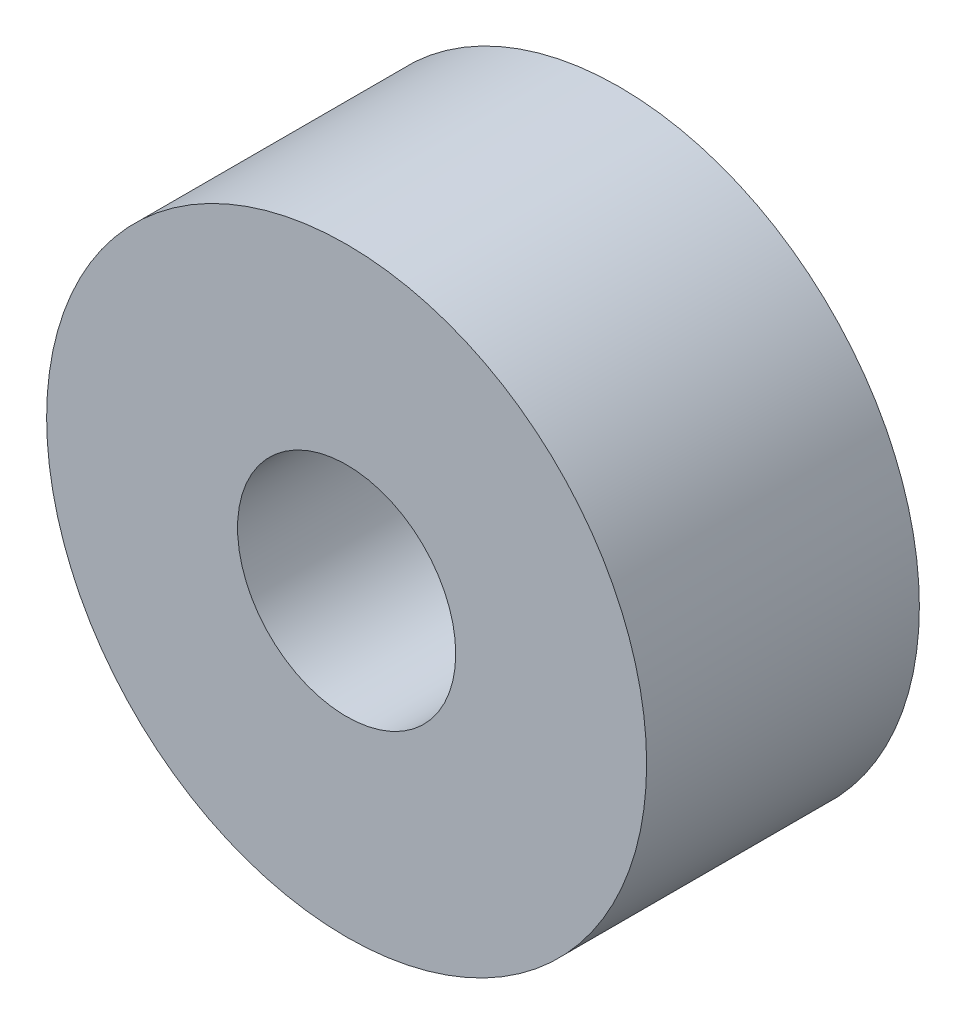
SolidWorks part; units mm, degrees
ref_plane "정면" through (0, 0, 0) normal (0, 0, 1) x (1, 0, 0)
ref_plane "윗면" through (0, 0, 0) normal (0, 1, 0) x (1, 0, 0)
ref_plane "우측면" through (0, 0, 0) normal (1, 0, 0) x (0, 0, -1)
sketch "스케치1" plane through (0, 0, 0) normal (0, 0, 1) x (1, 0, 0)
  circle A0 centre (0, 0) radius 11
  circle A1 centre (0, 0) radius 4
  dimension "D1" = 22
  dimension "D2" = 8
extrude "보스-돌출1" add sketch "스케치1" along normal blind 10
